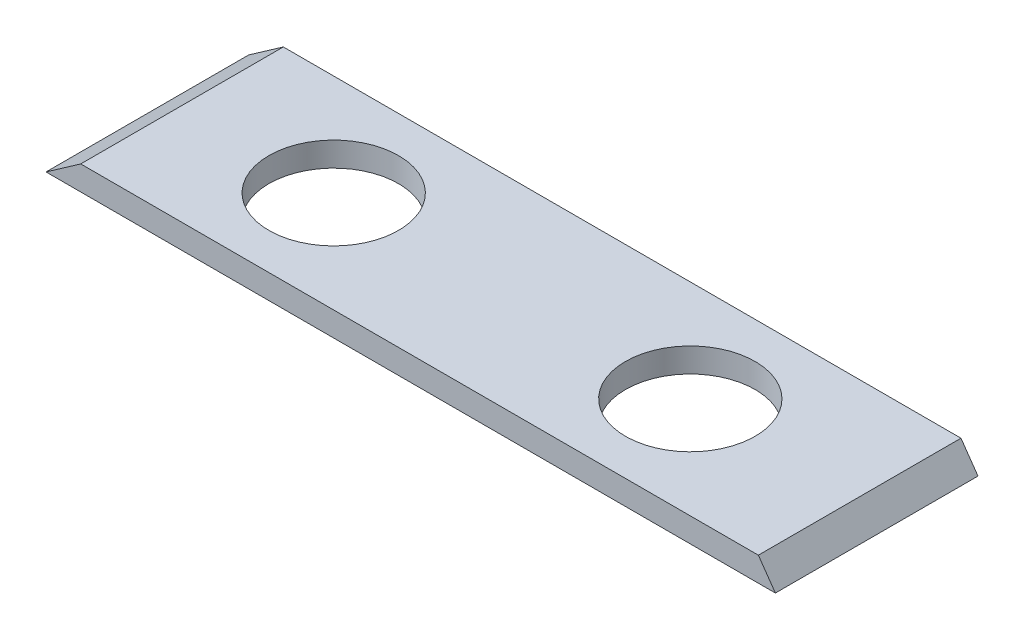
SolidWorks part; units mm, degrees
material "3.3320 (EN-AW 5019)"
ref_plane "Спереди" through (0, 0, 0) normal (0, 0, 1) x (1, 0, 0)
ref_plane "Сверху" through (0, 0, 0) normal (0, 1, 0) x (1, 0, 0)
ref_plane "Справа" through (0, 0, 0) normal (1, 0, 0) x (0, 0, -1)
sketch "Эскиз2" plane through (0, 0, 0) normal (0, 0, 1) x (1, 0, 0)
  line L0 (-45, 0) -> (45, 0)
  line L1 (45, 0) -> (42.8994, 3)
  line L2 (42.8994, 3) -> (-40.7156, 3)
  line L3 (-40.7156, 3) -> (-45, 0)
  line L4 (-45, 0) -> (-45, 51.2905) construction
  line L5 (45, 0) -> (45, 40.4179) construction
  dimension "D1" = 90
  dimension "D2" = 35
  dimension "D3" = 55
  dimension "D4" = 3
extrude "Бобышка-Вытянуть1" add sketch "Эскиз2" along normal blind 25
sketch "Эскиз3" plane through (0, 3, 0) normal (0, 1, 0) x (1, 0, 0)
  line L0 (0, 0) -> (0, -25) construction
  line L1 (42.8994, -25) -> (-40.7156, -25) construction
  line L2 (42.8994, -12.5) -> (-40.7156, -12.5) construction
  line L3 (42.8994, -25) -> (42.8994, 0) construction
  line L4 (-40.7156, -25) -> (-40.7156, 0) construction
  circle A0 centre (-22, -12.5) radius 8
  circle A1 centre (22, -12.5) radius 8
  dimension "D3" = 16
  dimension "D1" = 44
  dimension "D2" = 22
extrude "Вырез-Вытянуть2" cut sketch "Эскиз3" against normal through all contours A1 | A0
